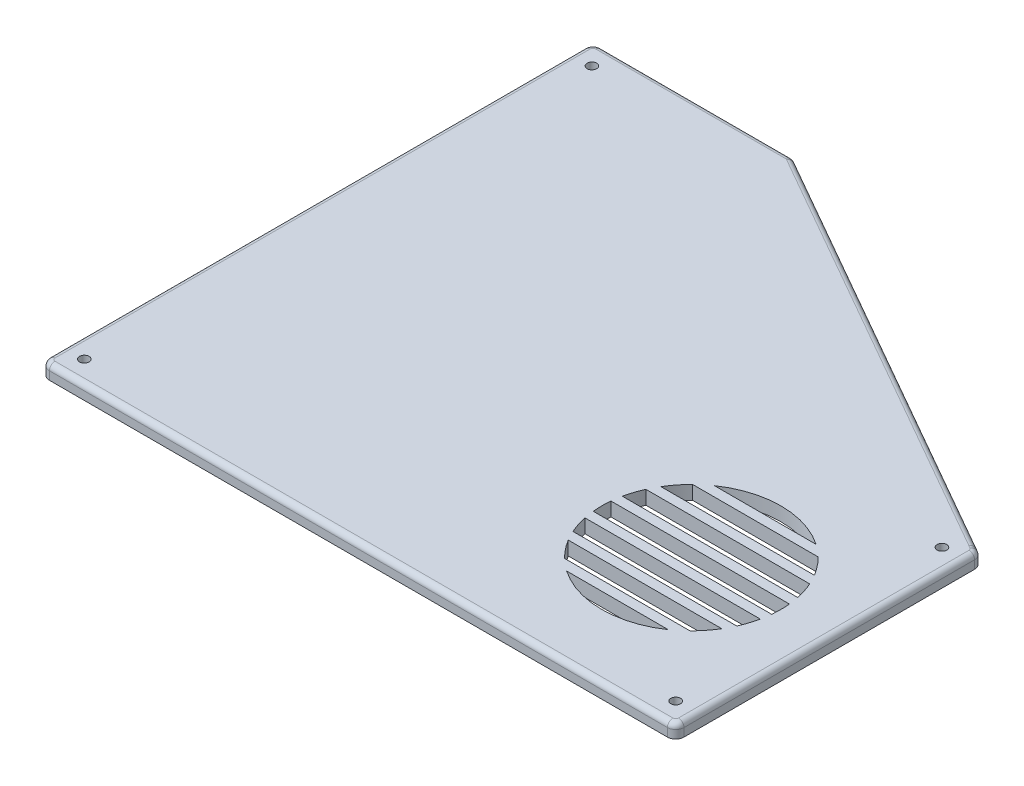
SolidWorks part; units mm, degrees
ref_plane "Front Plane" through (0, 0, 0) normal (0, 0, 1) x (1, 0, 0)
ref_plane "Top Plane" through (0, 0, 0) normal (0, 1, 0) x (1, 0, 0)
ref_plane "Right Plane" through (0, 0, 0) normal (1, 0, 0) x (0, 0, -1)
sketch "Sketch1" plane through (0, 0, 0) normal (0, 1, 0) x (1, 0, 0)
  line L0 (-115, 97) -> (-115, -97)
  line L1 (-112, -100) -> (112, -100)
  line L2 (115, -97) -> (115, 8.3268)
  line L3 (113.4894, 10.931) -> (112.4823, 11.507)
  line L4 (112.4823, 11.507) -> (-41.6945, 99.6048)
  line L5 (-43.1829, 100) -> (-112, 100)
  circle A0 centre (-107.358, 91.9967) radius 1.75
  circle A1 centre (107.1716, 4.3383) radius 1.75
  circle A2 centre (107.1716, -92.1716) radius 1.75
  circle A3 centre (-107.3206, -92.03) radius 1.75
  arc A4 (-115, -97) -> (-112, -100) centre (-112, -97) ccw
  arc A5 (112, -100) -> (115, -97) centre (112, -97) ccw
  arc A6 (115, 8.3268) -> (113.4894, 10.931) centre (112, 8.3268) ccw
  arc A7 (-41.6945, 99.6048) -> (-43.1829, 100) centre (-43.1829, 97) ccw
  arc A8 (-112, 100) -> (-115, 97) centre (-112, 97) ccw
extrude "Boss-Extrude1" add sketch "Sketch1" along normal blind 5
sketch "Sketch2" plane through (0, 5, 0) normal (0, 1, 0) x (1, 0, 0)
  line L0 (115, -97) -> (115, 8.3268) construction
  line L1 (26.802, -31.1184) -> (103.198, -31.1184)
  line L2 (26.802, -41.1184) -> (103.198, -41.1184)
  line L3 (26.802, -41.1184) -> (26.802, -47.5548)
  line L4 (26.802, -47.5548) -> (103.198, -47.5548)
  line L5 (103.198, -41.1184) -> (103.198, -47.5548)
  line L6 (26.802, -41.1184) -> (103.198, -47.5548) construction
  line L7 (26.802, -47.5548) -> (103.198, -41.1184) construction
  line L8 (26.802, -31.1184) -> (26.802, -37.5548)
  line L9 (26.802, -37.5548) -> (103.198, -37.5548)
  line L10 (103.198, -31.1184) -> (103.198, -37.5548)
  line L11 (26.802, -21.1184) -> (103.198, -21.1184)
  line L12 (26.802, -21.1184) -> (26.802, -27.5548)
  line L13 (26.802, -27.5548) -> (103.198, -27.5548)
  line L14 (103.198, -21.1184) -> (103.198, -27.5548)
  line L15 (26.802, -11.1184) -> (103.198, -11.1184)
  line L16 (26.802, -11.1184) -> (26.802, -17.5548)
  line L17 (26.802, -17.5548) -> (103.198, -17.5548)
  line L18 (103.198, -11.1184) -> (103.198, -17.5548)
  line L19 (26.802, -51.1184) -> (103.198, -51.1184)
  line L20 (26.802, -51.1184) -> (26.802, -57.5548)
  line L21 (26.802, -57.5548) -> (103.198, -57.5548)
  line L22 (103.198, -51.1184) -> (103.198, -57.5548)
  line L23 (26.802, -61.1184) -> (103.198, -61.1184)
  line L24 (26.802, -61.1184) -> (26.802, -67.5548)
  line L25 (26.802, -67.5548) -> (103.198, -67.5548)
  line L26 (103.198, -61.1184) -> (103.198, -67.5548)
  line L27 (26.802, -71.1184) -> (103.198, -71.1184)
  line L28 (26.802, -71.1184) -> (26.802, -77.5548)
  line L29 (26.802, -77.5548) -> (103.198, -77.5548)
  line L30 (103.198, -71.1184) -> (103.198, -77.5548)
  circle A0 centre (65, -44.3366) radius 32.5
  dimension "D1" = 65
  dimension "D2" = 50
  dimension "D3" = 6.4364
  dimension "D4" = 4
  dimension "D5" = 4
extrude "Cut-Extrude1" cut sketch "Sketch2" against normal blind 5 contours L17 A0 | L13 A0 L11 | L9 A0 L1 | L4 A0 L2 | L21 A0 L19 | L25 A0 L23 | L27 A0
fillet "Fillet2" radius 2 11 edges at (-114.1213, 5, 99.1213) (0, 5, 100) (114.1213, 5, 99.1213) (115, 5, 44.3366) (112.9858, 5, -11.219) (114.595, 5, -9.8322) (-42.4129, 5, -99.8995) (35.3939, 5, -55.5559) (-115, 5, 0) (-114.1213, 5, -99.1213) (-77.5915, 5, -100)
